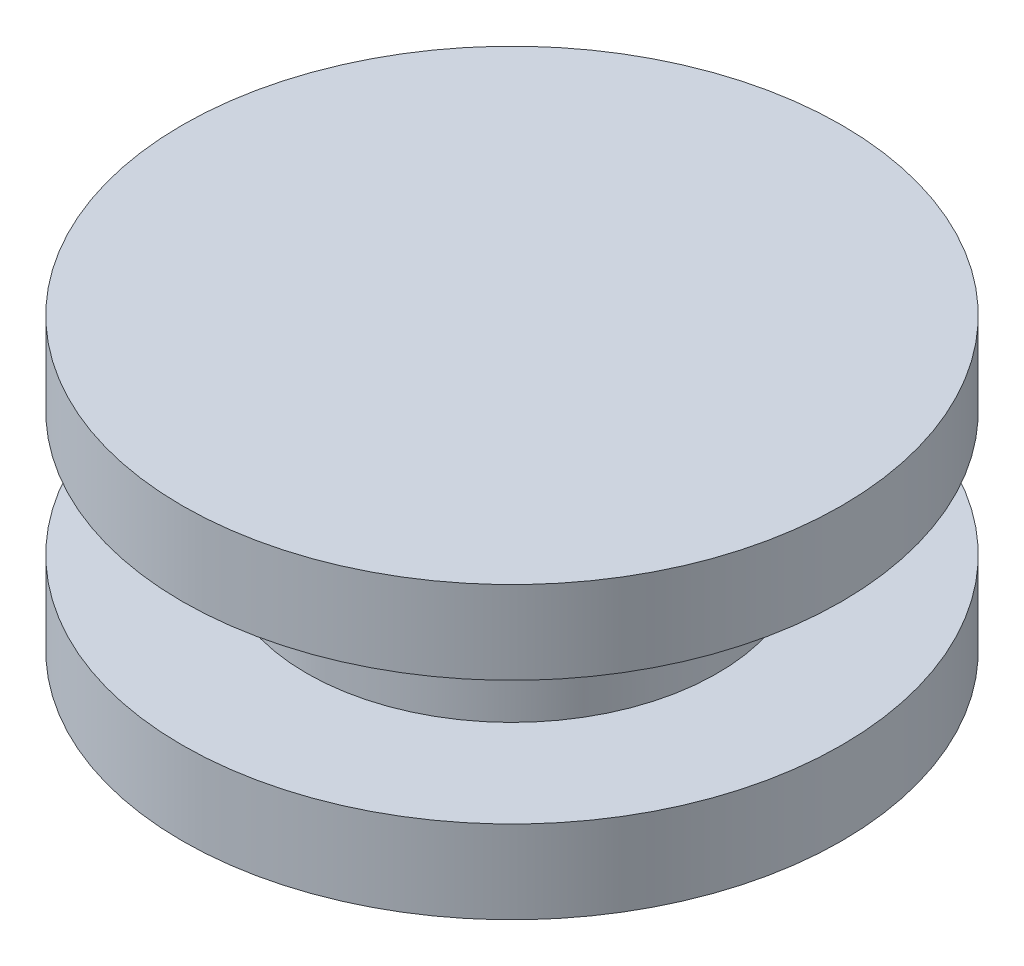
SolidWorks part; units mm, degrees
ref_plane "Front Plane" through (0, 0, 0) normal (0, 0, 1) x (1, 0, 0)
ref_plane "Top Plane" through (0, 0, 0) normal (0, 1, 0) x (1, 0, 0)
ref_plane "Right Plane" through (0, 0, 0) normal (1, 0, 0) x (0, 0, -1)
sketch "Sketch1" plane through (0, 0, 0) normal (0, 1, 0) x (1, 0, 0)
  circle A0 centre (0, 0) radius 2.475
  dimension "D1" = 4.95
extrude "Boss-Extrude1" add sketch "Sketch1" along normal mid plane 1.5
sketch "Sketch3" plane through (0, 0.75, 0) normal (0, 1, 0) x (1, 0, 0)
  circle A2 centre (0, 0) radius 3.975
  circle A3 centre (0, 0) radius 3.975
  dimension "D1" = 1.5
extrude "Boss-Extrude2" add sketch "Sketch3" along normal blind 1
mirror "Mirror1" about plane through (0, 0, 0) normal (0, 1, 0) of "Boss-Extrude2"
